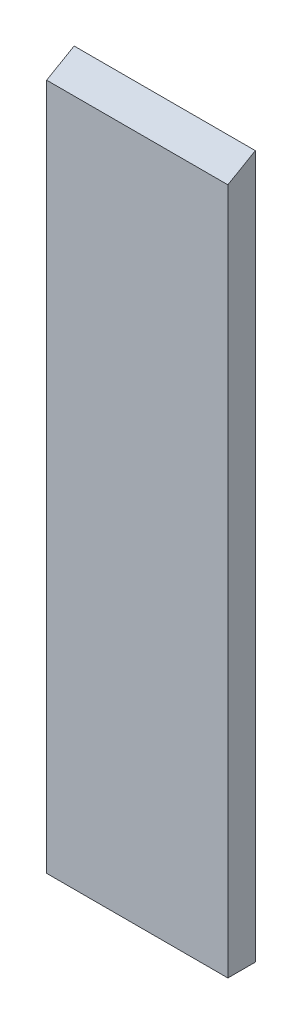
SolidWorks part; units mm, degrees
ref_plane "Alzado" through (0, 0, 0) normal (0, 0, 1) x (1, 0, 0)
ref_plane "Planta" through (0, 0, 0) normal (0, 1, 0) x (1, 0, 0)
ref_plane "Vista lateral" through (0, 0, 0) normal (1, 0, 0) x (0, 0, -1)
sketch "Croquis1" plane through (0, 0, 0) normal (0, 1, 0) x (1, 0, 0)
  line L1 (-9.9219, 44.6777) -> (190.0781, 44.6777)
  line L2 (-9.9219, 44.6777) -> (-9.9219, 14.3677)
  line L3 (-9.9219, 14.3677) -> (190.0781, 14.3677)
  line L4 (190.0781, 44.6777) -> (190.0781, 14.3677)
  dimension "D1" = 200
  dimension "D2" = 30.31
extrude "Saliente-Extruir1" add sketch "Croquis1" along normal blind 775.633
sketch "Croquis5" plane through (190.0781, 0, 0) normal (1, 0, 0) x (0, 0, -1)
  line L3 (14.3677, 775.633) -> (44.6777, 775.633)
  line L8 (44.6777, 775.633) -> (14.3677, 758.1315)
  line L9 (14.3677, 775.633) -> (14.3677, 0) construction
  line L10 (14.3677, 758.1315) -> (14.3677, 775.633)
  dimension "D1" = 35
extrude "Cortar-Extruir1" cut sketch "Croquis5" against normal blind 360
